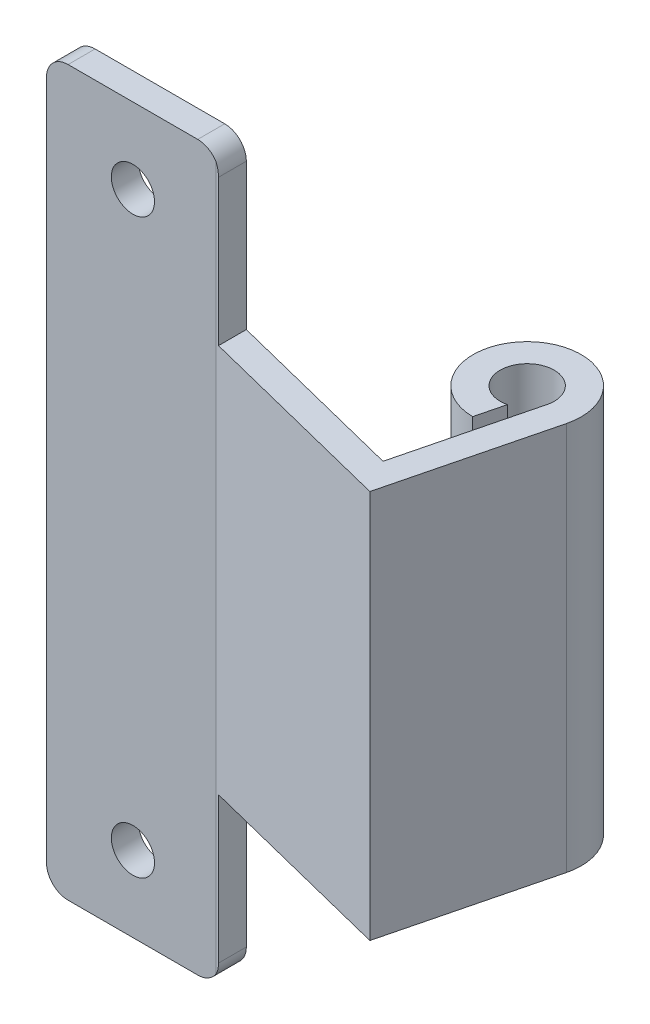
SolidWorks part; units mm, degrees
material "Plain Carbon Steel"
ref_plane "Front" through (0, 0, 0) normal (0, 0, 1) x (1, 0, 0)
ref_plane "Top" through (0, 0, 0) normal (0, 1, 0) x (1, 0, 0)
ref_plane "Right" through (0, 0, 0) normal (1, 0, 0) x (0, 0, -1)
sketch "Sketch1" plane through (0, 0, 0) normal (0, 1, 0) x (1, 0, 0)
  line L0 (4.8499, -1.2157) -> (1.2027, -15.7656)
  line L1 (1.2027, -15.7656) -> (-17.8086, -11)
  line L2 (-17.8086, -11) -> (-33.5, -11)
  line L3 (2.425, -0.6079) -> (-0.6144, -12.7327)
  line L4 (-0.6144, -12.7327) -> (-17.5, -8.5)
  line L5 (-17.5, -8.5) -> (-33.5, -8.5)
  line L6 (-33.5, -8.5) -> (-33.5, -11)
  line L7 (0.6008, -2.4267) -> (-0.0442, -4.9998)
  arc A0 (4.8499, -1.2157) -> (-0.0442, -4.9998) centre (0, 0) ccw
  arc A1 (2.425, -0.6079) -> (0.6008, -2.4267) centre (0, 0) ccw
  point P1 (1.3929, -15.7499)
  dimension "D1" = 5
  dimension "D2" = 10
  dimension "D7" = 20
  dimension "D8" = 16
  dimension "D3" = 2.5
  dimension "D4" = 2.5
  dimension "D5" = 2.5
  dimension "D6" = 38.5
  dimension "D9" = 16
extrude "Boss-Extrude1" add sketch "Sketch1" along normal mid plane 67
sketch "Sketch3" plane through (0, 0, 8.5) normal (0, 0, -1) x (-1, 0, 0)
  line L0 (17.5, 33.5) -> (17.5, -33.5) construction
  line L1 (17.5, 18) -> (-20.2129, 18)
  line L2 (17.5, 18) -> (17.5, 50.8065)
  line L3 (17.5, 50.8065) -> (-20.2129, 50.8065)
  line L4 (-20.2129, 18) -> (-20.2129, 50.8065)
  line L5 (0, 0) -> (-16.1774, 0) construction
  line L6 (-20.2129, -18) -> (-20.2129, -50.8065)
  line L7 (17.5, -50.8065) -> (-20.2129, -50.8065)
  line L8 (17.5, -18) -> (17.5, -50.8065)
  line L9 (17.5, -18) -> (-20.2129, -18)
  dimension "D1" = 36
extrude "Cut-Extrude1" cut sketch "Sketch3" against normal through all and the other way through all
sketch "Sketch4" plane through (0, 0, 8.5) normal (0, 0, -1) x (-1, 0, 0)
  line L0 (33.5, 0) -> (43.457, 0) construction
  line L1 (33.5, 33.5) -> (33.5, -33.5) construction
  line L2 (17.5, 33.5) -> (33.5, 33.5) construction
  circle A0 centre (25.5, 26.5) radius 2
  circle A1 centre (25.5, -26.5) radius 2
  dimension "D1" = 6
  dimension "D2" = 5
  dimension "D3" = 4
extrude "Cut-Extrude2" cut sketch "Sketch4" against normal through all
fillet "Fillet1" radius 2 4 edges at (-17.5, -33.5, 9.7887) (-33.5, -33.5, 9.75) (-33.5, 33.5, 9.75) (-17.5, 33.5, 9.7887)
ref_plane "Plane1" through (-25.5, 0, 0) normal (1, 0, 0) x (0, 0, -1)
